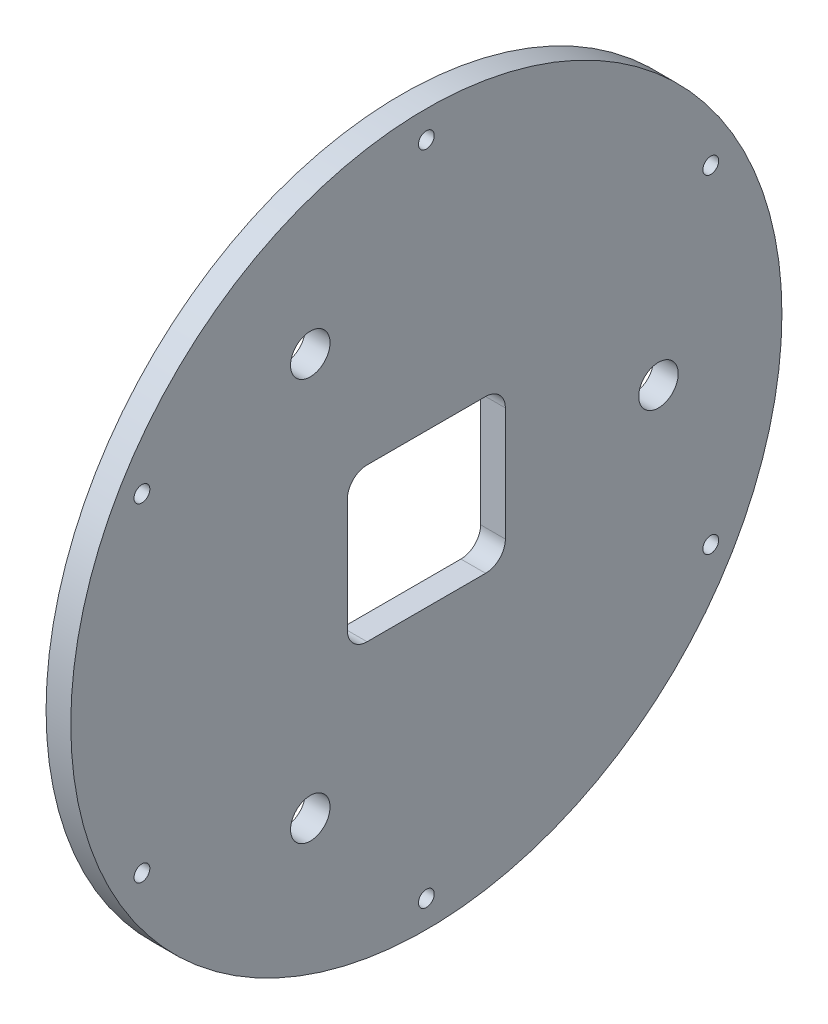
SolidWorks part; units mm, degrees
material "Balsa"
ref_plane "Front Plane" through (0, 0, 0) normal (0, 0, 1) x (1, 0, 0)
ref_plane "Top Plane" through (0, 0, 0) normal (0, 1, 0) x (1, 0, 0)
ref_plane "Right Plane" through (0, 0, 0) normal (1, 0, 0) x (0, 0, -1)
sketch "Sketch4" plane through (0, 0, 0) normal (1, 0, 0) x (0, 0, -1)
  circle A0 centre (0, 0) radius 72
  dimension "D1" = 144
sketch "Sketch2" plane through (0, 0, 0) normal (1, 0, 0) x (0, 0, -1)
  line L0 (0, 0) -> (0, 77.0354) construction
  circle A0 centre (0, 0) radius 66.5 construction
  circle A1 centre (0, 66.5) radius 1.6
  circle A2 centre (57.5907, 33.25) radius 1.6
  circle A3 centre (57.5907, -33.25) radius 1.6
  circle A4 centre (0, -66.5) radius 1.6
  circle A5 centre (-57.5907, -33.25) radius 1.6
  circle A6 centre (-57.5907, 33.25) radius 1.6
  point P17 (0, 0)
  dimension "D3" = 3.2
  dimension "D1" = 66.5
  dimension "D2" = 6
sketch "Sketch3" plane through (0, 0, 0) normal (1, 0, 0) x (0, 0, -1)
  line L0 (-4.7792, 0) -> (94.0848, 0) construction
  circle A2 centre (47, 0) radius 4
  circle A3 centre (-23.5, -40.7032) radius 4
  circle A4 centre (-23.5, 40.7032) radius 4
  dimension "D1" = 47
  dimension "D3" = 8
  dimension "D5" = 3
extrude "Boss-Extrude3" add sketch "Sketch4" along normal blind 5
extrude "Cut-Extrude6" cut sketch "Sketch3" along normal through all
extrude "Cut-Extrude1" cut sketch "Sketch2" along normal through all
sketch "Sketch1" plane through (0, 0, 0) normal (1, 0, 0) x (0, 0, -1)
  line L0 (0, 0) -> (16, 0) construction
  line L1 (-12, 15.5) -> (12, 15.5)
  line L2 (-16, 11.5) -> (-16, -11.5)
  line L3 (-12, -15.5) -> (12, -15.5)
  line L4 (16, 11.5) -> (16, -11.5)
  line L5 (0, 0) -> (0, 15.5) construction
  arc A5 (-12, -15.5) -> (-16, -11.5) centre (-12, -11.5) cw
  arc A6 (12, -15.5) -> (16, -11.5) centre (12, -11.5) ccw
  arc A7 (16, 11.5) -> (12, 15.5) centre (12, 11.5) ccw
  arc A8 (-12, 15.5) -> (-16, 11.5) centre (-12, 11.5) ccw
  point P13 (-12, 15.5)
  point P29 (-16, -15.5)
  point P32 (16, -15.5)
  point P35 (16, 15.5)
  point P38 (-16, 15.5)
  dimension "D2" = 32
  dimension "D12" = 4
  dimension "D6" = 31
extrude "gopro" cut sketch "Sketch1" along normal through all
